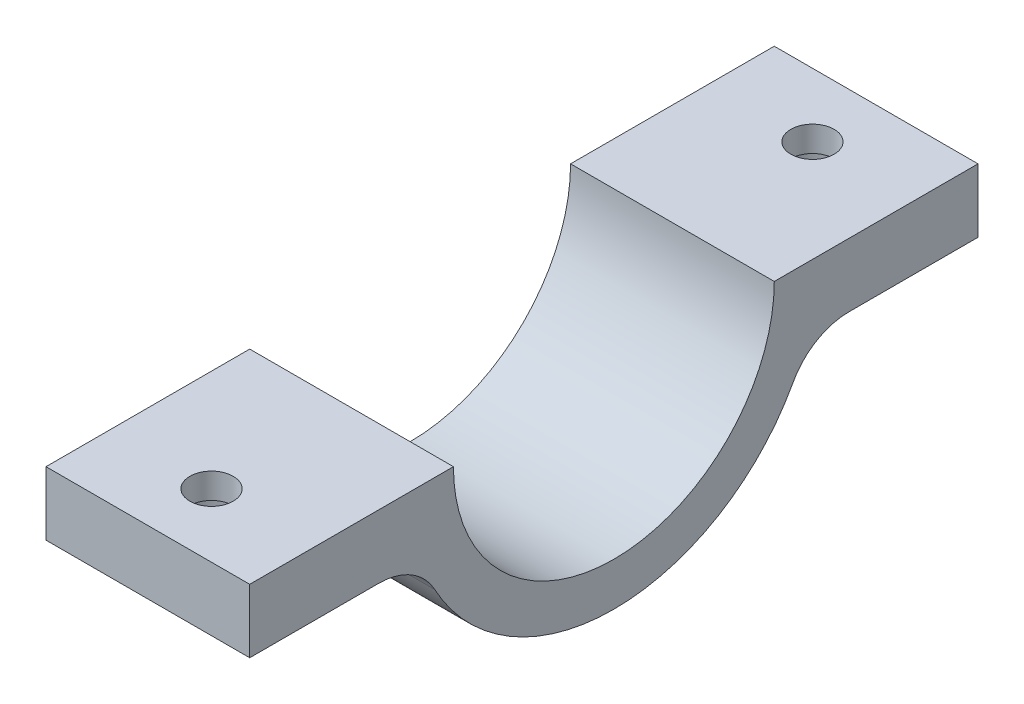
SolidWorks part; units mm, degrees
ref_plane "Front Plane" through (0, 0, 0) normal (0, 0, 1) x (1, 0, 0)
ref_plane "Top Plane" through (0, 0, 0) normal (0, 1, 0) x (1, 0, 0)
ref_plane "Right Plane" through (0, 0, 0) normal (1, 0, 0) x (0, 0, -1)
sketch "Sketch2" plane through (0, 0, 0) normal (1, 0, 0) x (0, 0, -1)
  line L0 (-55.1948, 0) -> (55.1948, 0) construction
  line L1 (-12.6, 0) -> (-28.6, 0)
  line L2 (-28.6, 0) -> (-28.6, -5)
  line L3 (-28.6, -5) -> (-15.1987, -5)
  line L4 (0, 0) -> (0, -26.7431) construction
  line L5 (12.6, 0) -> (28.6, 0)
  line L6 (28.6, -5) -> (15.1987, -5)
  line L7 (28.6, 0) -> (28.6, -5)
  arc A0 (12.6, 0) -> (-12.6, 0) centre (0, 0) cw
  arc A1 (15.1987, -5) -> (-15.1987, -5) centre (0, 0) cw
  point P7 (0, 0)
  dimension "D1" = 12.6
  dimension "D2" = 5
  dimension "D4" = 16
  dimension "D3" = 16
extrude "Mount_Bottom" add sketch "Sketch2" along normal mid plane 16
fillet "Fastening_Filet_Bottom" radius 5 2 edges at (0, -5, 15.1987) (0, -5, -15.1987)
sketch "Sketch6" plane through (0, -5, 0) normal (0, -1, 0) x (1, 0, 0)
  line L0 (8, 28.6) -> (-8, 28.6) construction
  line L2 (0, 0) -> (12.6299, 0) construction
  line L3 (0, 0) -> (0, 8.4396) construction
  point P0 (0, 23.6)
  point P8 (0, -23.6)
  point P17 (0, 0)
  point P18 (0, 0)
  point P19 (0, 23.6)
  point P20 (0, -23.6)
  point P21 (0, 0)
  dimension "D1" = 5
hole_wizard "CBORE for M3 SHCS1" positions "Sketch6" profile "Sketch7" counterbore size "M3" standard "ANSI Metric" end condition through all
sketch "Sketch7" plane through (0, -5, 23.6) normal (1, 0, 0) x (0, 0, -1)
  line L0 (0, 0) -> (0, 5)
  line L1 (0, 5) -> (1.7, 5)
  line L3 (1.7, 5) -> (1.7, 3)
  line L4 (1.7, 3) -> (3.25, 3)
  line L5 (3.25, 3) -> (3.25, 0)
  line L7 (3.25, 0) -> (0, 0)
  line L11 (0, -6.35) -> (0, 107.95) construction
  dimension "Thru Hole Dia." = 3.4
  dimension "Thru Hole Depth" = 5
  dimension "C'Bore Dia." = 6.5
  dimension "C'Bore Depth" = 3
